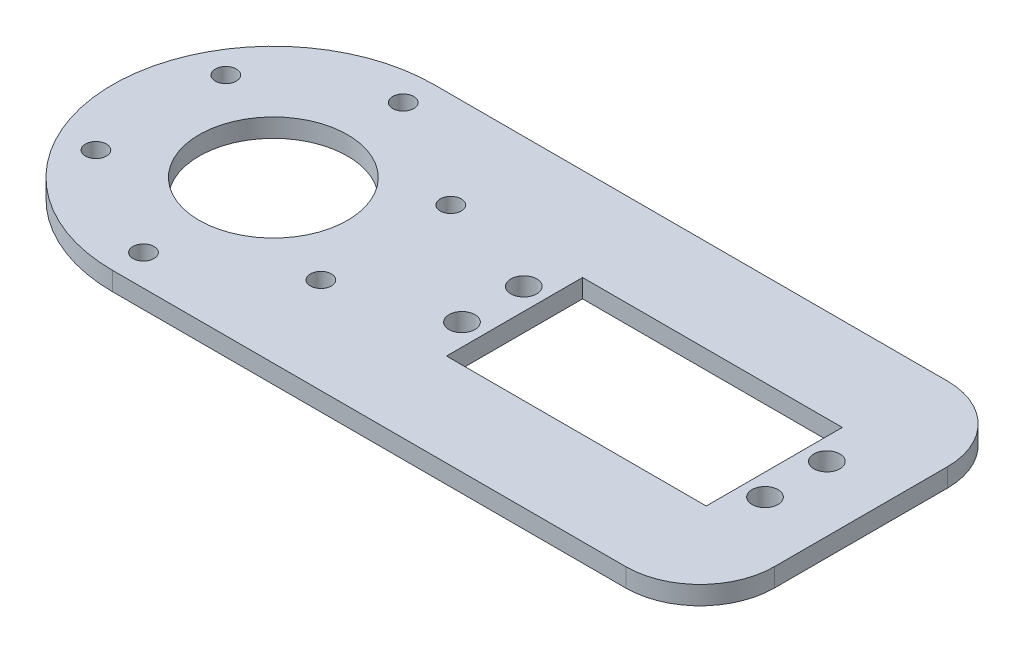
SolidWorks part; units mm, degrees
material "C-玻璃纤维"
ref_plane "前视基准面" through (0, 0, 0) normal (0, 0, 1) x (1, 0, 0)
ref_plane "上视基准面" through (0, 0, 0) normal (0, 1, 0) x (1, 0, 0)
ref_plane "右视基准面" through (0, 0, 0) normal (1, 0, 0) x (0, 0, -1)
other "Configuration Table"
sketch "草图1" plane through (0, 0, 0) normal (0, 1, 0) x (1, 0, 0)
  line L0 (-61.3781, 0) -> (104.1685, 0) construction
  line L1 (0, -26) -> (95, -26)
  line L3 (0, 26) -> (95, 26)
  line L4 (95, -26) -> (95, 26)
  line L5 (0, 76.4849) -> (0, -66.5007) construction
  line L6 (60, 46.7224) -> (60, -36.8696) construction
  line L7 (0, 0) -> (0, -21) construction
  line L8 (39, -11) -> (81, -11)
  line L9 (39, -11) -> (39, 11)
  line L10 (39, 11) -> (81, 11)
  line L11 (81, -11) -> (81, 11)
  line L12 (60, 11) -> (60, -11) construction
  line L13 (39, 0) -> (81, 0) construction
  circle A0 centre (0, 0) radius 12
  circle A2 centre (0, -21) radius 1.7
  arc A3 (0, 26) -> (0, -26) centre (0, 0) ccw
  circle A4 centre (35.5, 5) radius 2.1
  circle A5 centre (35.5, -5) radius 2.1
  circle A6 centre (84.5, -5) radius 2.1
  circle A7 centre (84.5, 5) radius 2.1
  circle A8 centre (-18.1865, -10.5) radius 1.7
  circle A9 centre (-18.1865, 10.5) radius 1.7
  circle A10 centre (0, 21) radius 1.7
  circle A11 centre (18.1865, 10.5) radius 1.7
  circle A12 centre (18.1865, -10.5) radius 1.7
  point P23 (60, 0)
  point P41 (0, 0)
  dimension "D1" = 24
  dimension "D2" = 3.4
  dimension "D6" = 4.2
  dimension "D3" = 6
  dimension "D4" = 52
  dimension "D5" = 60
  dimension "D7" = 10
  dimension "D8" = 24.5
  dimension "D9" = 22
  dimension "D10" = 42
  dimension "D11" = 35
  dimension "D13" = 21
extrude "凸台-拉伸1" add sketch "草图1" along normal blind 3
fillet "圆角1" radius 12 2 edges at (95, 1.5, -26) (95, 1.5, 26)
